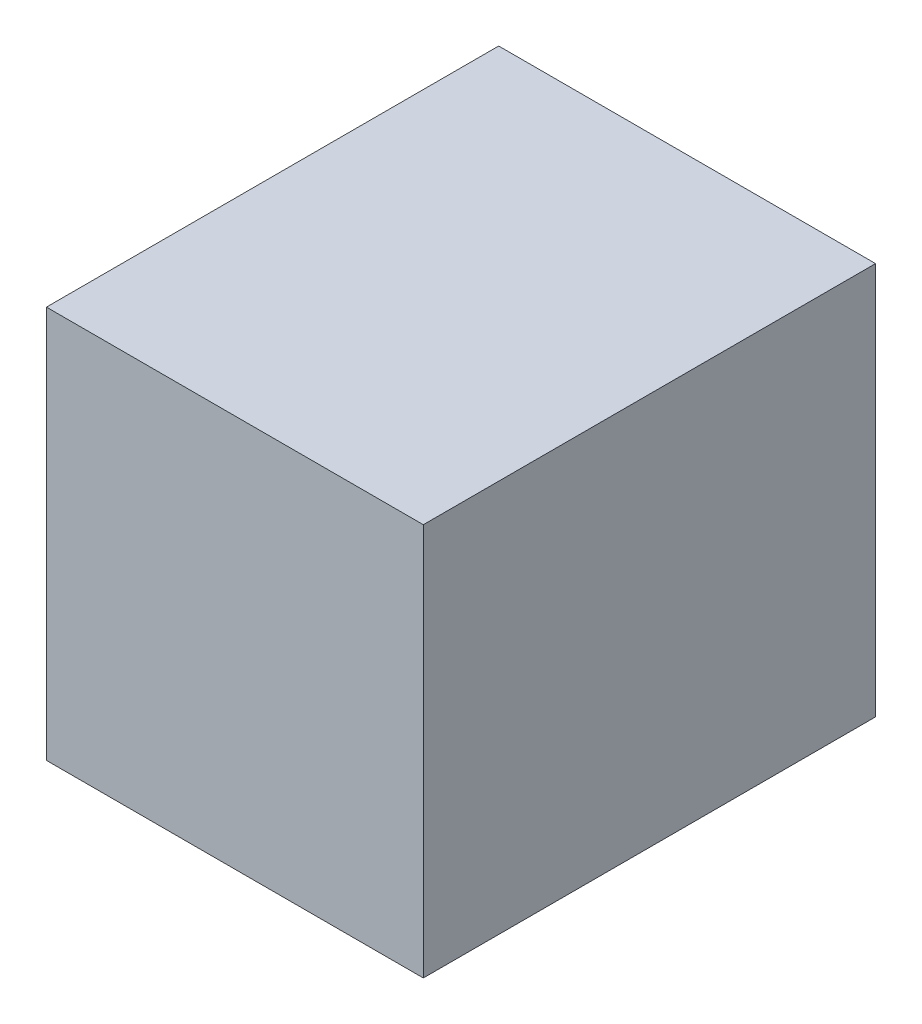
SolidWorks part; units mm, degrees
ref_plane "Front Plane" through (0, 0, 0) normal (0, 0, 1) x (1, 0, 0)
ref_plane "Top Plane" through (0, 0, 0) normal (0, 1, 0) x (1, 0, 0)
ref_plane "Right Plane" through (0, 0, 0) normal (1, 0, 0) x (0, 0, -1)
sketch "Sketch1" plane through (0, 0, 0) normal (0, 1, 0) x (1, 0, 0)
  line L1 (30, -36) -> (-30, -36)
  line L2 (30, -36) -> (30, 36)
  line L3 (30, 36) -> (-30, 36)
  line L4 (-30, -36) -> (-30, 36)
  line L5 (30, -36) -> (-30, 36) construction
  line L6 (30, 36) -> (-30, -36) construction
  point P0 (0, 0)
  dimension "D1" = 60
  dimension "D2" = 72
extrude "Boss-Extrude1" add sketch "Sketch1" along normal blind 62.5
